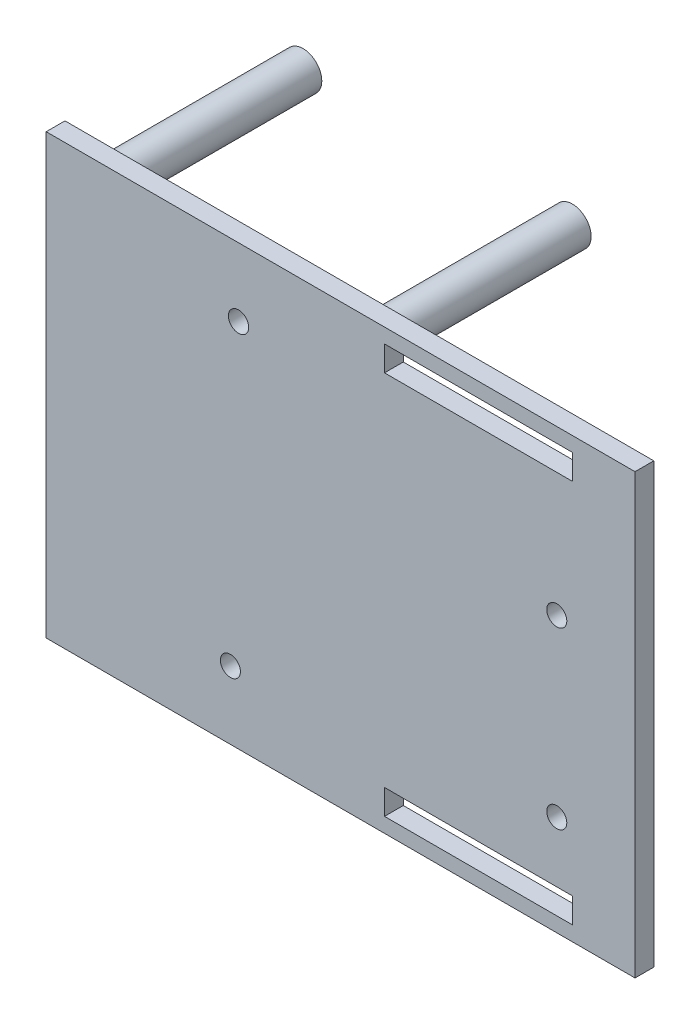
SolidWorks part; units mm, degrees
ref_plane "Front Plane" through (0, 0, 0) normal (0, 0, 1) x (1, 0, 0)
ref_plane "Top Plane" through (0, 0, 0) normal (0, 1, 0) x (1, 0, 0)
ref_plane "Right Plane" through (0, 0, 0) normal (1, 0, 0) x (0, 0, -1)
sketch "Sketch1" plane through (0, 0, 0) normal (0, 0, 1) x (1, 0, 0)
  line L1 (0, 0) -> (94, 0)
  line L2 (0, 0) -> (0, 70)
  line L3 (0, 70) -> (94, 70)
  line L4 (94, 0) -> (94, 70)
  dimension "D1" = 94
  dimension "D2" = 70
extrude "Boss-Extrude2" add sketch "Sketch1" along normal blind 3
sketch "Sketch3" plane through (0, 0, 3) normal (0, 0, 1) x (1, 0, 0)
  line L0 (94, 0) -> (49, 0) construction
  line L1 (0, 0) -> (94, 0) construction
  line L2 (49, 0) -> (49, 6) construction
  line L3 (49, 70) -> (49, 64) construction
  line L4 (94, 70) -> (0, 70) construction
  line L5 (49, 64) -> (6, 64) construction
  circle A0 centre (49, 6) radius 3
  circle A1 centre (49, 64) radius 3
  circle A2 centre (6, 64) radius 3
extrude "Boss-Extrude5" add sketch "Sketch3" against normal blind 35
sketch "Sketch7" plane through (0, 0, -32) normal (0, 0, -1) x (-1, 0, 0)
  circle A0 centre (-49, 6) radius 1.6026
extrude "Cut-Extrude1" cut sketch "Sketch7" against normal blind 5
sketch "Sketch8" plane through (0, 0, -32) normal (0, 0, -1) x (-1, 0, 0)
  circle A0 centre (-6, 64) radius 1.6
extrude "Cut-Extrude2" cut sketch "Sketch8" against normal blind 5
sketch "Sketch9" plane through (0, 0, -32) normal (0, 0, -1) x (-1, 0, 0)
  circle A0 centre (-49, 64) radius 1.6
extrude "Cut-Extrude3" cut sketch "Sketch9" against normal blind 5
sketch "Sketch10" plane through (0, 0, 3) normal (0, 0, 1) x (1, 0, 0)
  line L0 (94, 70) -> (94, 61.65) construction
  line L1 (94, 0) -> (94, 70) construction
  line L2 (94, 0) -> (94, 8.35) construction
  line L3 (93.2563, 8.35) -> (-49906.7437, 8.35) construction
  line L4 (94, 61.65) -> (-49906, 61.65) construction
  line L5 (94, 61.65) -> (84.0082, 61.65) construction
  line L6 (94, 8.35) -> (84.0082, 8.35) construction
  line L7 (84.0082, 61.6658) -> (84.0082, -49938.3342) construction
  line L8 (84.0082, 61.65) -> (15.4082, 61.65) construction
  line L9 (15.4082, 61.65) -> (15.4082, -49938.35) construction
  line L10 (84.0082, 8.35) -> (15.4082, 8.35) construction
  line L11 (15.4082, 61.65) -> (29.4082, 61.65) construction
  line L12 (29.4082, 61.65) -> (29.4082, 10.85) construction
  line L13 (29.4082, 61.65) -> (30.7082, 61.65) construction
  line L14 (30.7082, 61.65) -> (30.7082, 59.1) construction
  line L15 (29.4082, 10.85) -> (29.4082, 8.35) construction
  line L16 (30.7082, 59.1) -> (81.5082, 59.1) construction
  line L17 (81.5082, 59.1) -> (81.5082, 43.9) construction
  line L18 (81.5082, 43.9) -> (81.5082, 15.9982) construction
  line L19 (84.0082, 61.65) -> (84.0082, 63.6658) construction
  line L20 (84.0082, 63.6658) -> (84.0082, 67.6658)
  line L21 (84.0082, 67.6658) -> (54.0082, 67.6658)
  line L22 (84.0082, 63.6658) -> (54.0082, 63.6658)
  line L23 (54.0082, 67.6658) -> (54.0082, 63.6658)
  line L24 (84.0082, 8.35) -> (84.0082, 6.35) construction
  line L25 (84.0082, 6.35) -> (84.0082, 2.35)
  line L26 (84.0082, 6.35) -> (54.0082, 6.35)
  line L27 (84.0082, 2.35) -> (54.0082, 2.35)
  line L28 (54.0082, 6.35) -> (54.0082, 2.35)
  circle A0 centre (29.4082, 10.85) radius 1.6
  circle A1 centre (30.7082, 59.1) radius 1.6192
  circle A2 centre (81.5082, 43.9) radius 1.6
  circle A3 centre (81.5082, 15.9982) radius 1.6
  point P40 (0, 0)
  dimension "D1" = 2.55
  dimension "D2" = 14
  dimension "D3" = 2.5
extrude "Cut-Extrude5" cut sketch "Sketch10" against normal blind 5 contours L21 L23 L22 L20 | L26 L28 L27 L25 | A0 | A3 | A2 | A1
